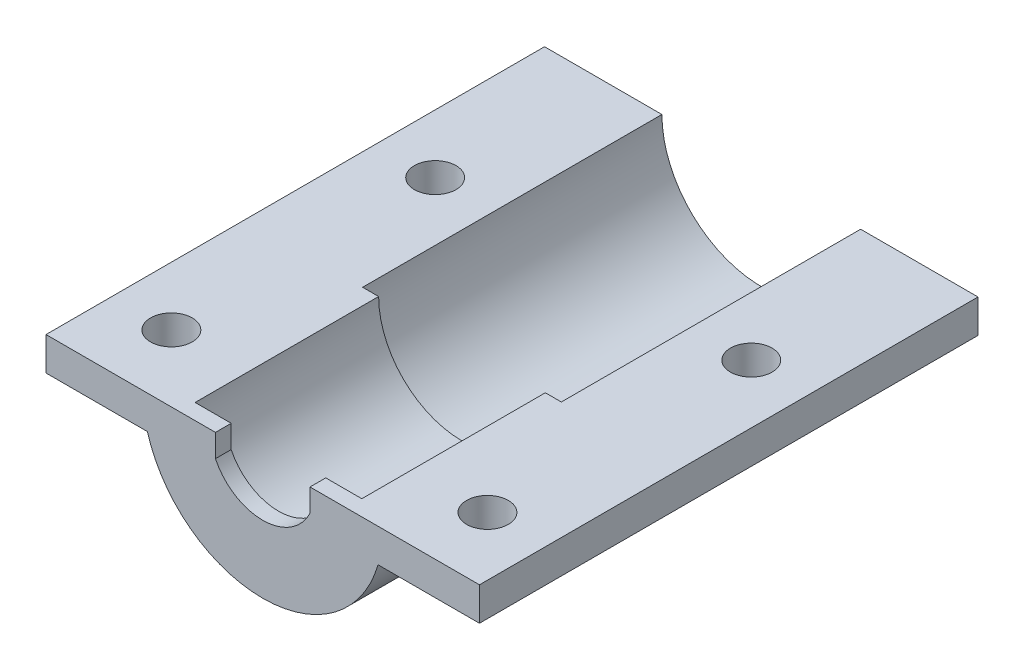
SolidWorks part; units mm, degrees
ref_plane "Front Plane" through (0, 0, 0) normal (0, 0, 1) x (1, 0, 0)
ref_plane "Top Plane" through (0, 0, 0) normal (0, 1, 0) x (1, 0, 0)
ref_plane "Right Plane" through (0, 0, 0) normal (1, 0, 0) x (0, 0, -1)
sketch "Sketch1" plane through (0, 0, 0) normal (0, 0, 1) x (1, 0, 0)
  line L0 (0, 0) -> (0, 45.72) construction
  line L3 (21.9604, 16.51) -> (41.275, 16.51)
  line L4 (41.275, 16.51) -> (41.275, 22.86)
  line L5 (41.275, 22.86) -> (15.875, 22.86)
  line L6 (-41.275, 16.51) -> (-41.275, 22.86)
  line L7 (-21.9604, 16.51) -> (-41.275, 16.51)
  line L9 (-15.875, 22.86) -> (-41.275, 22.86)
  arc A0 (-15.875, 22.86) -> (15.875, 22.86) centre (0, 22.86) ccw
  arc A1 (-21.9604, 16.51) -> (21.9604, 16.51) centre (0, 22.86) ccw
  point P13 (0, 22.86)
  dimension "D2" = 31.75
  dimension "D3" = 22.86
  dimension "D1" = 6.35
  dimension "D4" = 25.4
  dimension "D5" = 31.75
extrude "Boss-Extrude1" add sketch "Sketch1" along normal blind 94.9452
sketch "Sketch2" plane through (0, 0, 0) normal (0, 0, -1) x (-1, 0, 0)
  line L0 (15.875, 22.86) -> (41.275, 22.86) construction
  circle A0 centre (0, 22.86) radius 18.923
  dimension "D1" = 37.846
extrude "Cut-Extrude1" cut sketch "Sketch2" against normal blind 56.9976
sketch "Sketch3" plane through (0, 0, 94.9452) normal (0, 0, 1) x (1, 0, 0)
  line L0 (41.275, 22.86) -> (15.875, 22.86) construction
  line L1 (-15.875, 22.86) -> (-9.0043, 22.86)
  line L2 (-9.0043, 22.86) -> (-9.0043, 18.5217)
  line L3 (9.0043, 22.86) -> (9.0043, 18.5217)
  line L4 (9.0043, 22.86) -> (15.875, 22.86)
  arc A0 (-9.0043, 18.5217) -> (9.0043, 18.5217) centre (0, 22.86) ccw
  arc A2 (-15.875, 22.86) -> (15.875, 22.86) centre (0, 22.86) ccw
  dimension "D1" = 19.9898
  dimension "D2" = 18.0086
extrude "Boss-Extrude2" add sketch "Sketch3" against normal blind 2.9972
hole_wizard "Hole1" positions "Sketch5" profile "Sketch7" legacy end condition through all
sketch "Sketch5" plane through (0, 16.51, 0) normal (0, -1, 0) x (-1, 0, 0)
  line L3 (30.099, 0) -> (30.099, -34.4052) construction
  line L4 (41.275, 0) -> (21.9604, 0) construction
  line L5 (41.275, -94.9452) -> (21.9604, -94.9452) construction
  line L6 (41.275, -94.9452) -> (41.275, 0) construction
  line L7 (18.923, -56.9976) -> (18.923, 0) construction
  point P0 (30.099, -32.004)
  point P16 (30.099, -82.2452)
  dimension "D1" = 32.004
  dimension "D2" = 12.7
sketch "Sketch7" plane through (-30.099, 16.51, 32.004) normal (1, 0, 0) x (0, 0, -1)
  line L0 (0, 0) -> (0, 6.35)
  line L1 (0, 6.35) -> (3.9688, 6.35)
  line L2 (3.9688, 6.35) -> (3.9688, 0)
  line L3 (3.9688, 0) -> (0, 0)
  line L4 (0, 110) -> (0, -10) construction
  dimension "Diameter" = 7.9375
  dimension "Depth" = 6.35
ref_plane "Plane1" through (0, 0, 0) normal (1, 0, 0) x (0, 0, -1)
mirror "Mirror1" about plane through (0, 0, 0) normal (1, 0, 0) of "Hole1"
